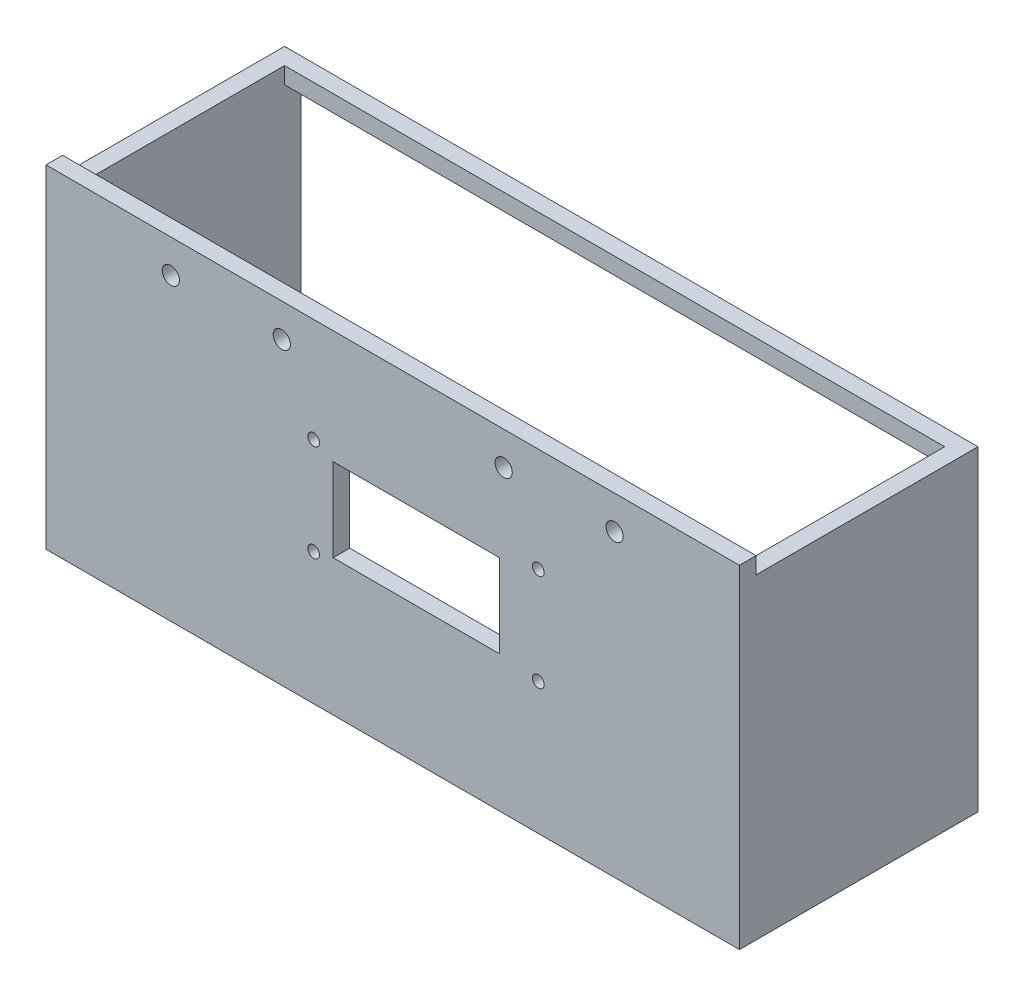
SolidWorks part; units mm, degrees
material "Thornel Mat VMA"
ref_plane "前视基准面" through (0, 0, 0) normal (0, 0, 1) x (1, 0, 0)
ref_plane "上视基准面" through (0, 0, 0) normal (0, 1, 0) x (1, 0, 0)
ref_plane "右视基准面" through (0, 0, 0) normal (1, 0, 0) x (0, 0, -1)
sketch "草图1" plane through (0, 0, 0) normal (0, 0, 1) x (1, 0, 0)
  line L1 (-62.5, 30) -> (62.5, 30)
  line L2 (-62.5, 30) -> (-62.5, -30)
  line L3 (-62.5, -30) -> (62.5, -30)
  line L4 (62.5, 30) -> (62.5, -30)
  line L5 (-62.5, 30) -> (62.5, -30) construction
  line L6 (-62.5, -30) -> (62.5, 30) construction
  line L7 (-14.25, 11.25) -> (26.25, 11.25) construction
  line L8 (-14.25, 11.25) -> (-14.25, -6.25) construction
  line L9 (-14.25, -6.25) -> (26.25, -6.25) construction
  line L10 (26.25, 11.25) -> (26.25, -6.25) construction
  line L11 (-10.75, 9.55) -> (19.25, 9.55)
  line L12 (-10.75, 9.55) -> (-10.75, -5.45)
  line L13 (-10.75, -5.45) -> (19.25, -5.45)
  line L14 (19.25, 9.55) -> (19.25, -5.45)
  line L15 (-10.75, 9.55) -> (19.25, -5.45) construction
  line L16 (-10.75, -5.45) -> (19.25, 9.55) construction
  circle A0 centre (-40, 24) radius 1.55
  circle A1 centre (-20, 24) radius 1.55
  circle A2 centre (20, 24) radius 1.55
  circle A3 centre (40, 24) radius 1.55
  circle A4 centre (-14.25, 11.25) radius 1.05
  circle A5 centre (-14.25, -6.25) radius 1.05
  circle A6 centre (26.25, 11.25) radius 1.05
  circle A7 centre (26.25, -6.25) radius 1.05
  point P0 (0, 0)
  point P22 (4.25, 2.05)
  dimension "D3" = 3.1
  dimension "D4" = 3.1
  dimension "D5" = 3.1
  dimension "D6" = 3.1
  dimension "D7" = 2.1
  dimension "D8" = 2.1
  dimension "D9" = 2.1
  dimension "D10" = 2.1
  dimension "D12" = 22.5
  dimension "D13" = 20
  dimension "D14" = 40
  dimension "D15" = 20
  dimension "D18" = 18.75
  dimension "D19" = 48.25
  dimension "D1" = 125
  dimension "D2" = 60
  dimension "D11" = 6
  dimension "D16" = 40.5
  dimension "D17" = 17.5
  dimension "D20" = 30
  dimension "D21" = 15
  dimension "D22" = 51.75
  dimension "D23" = 20.45
extrude "凸台-拉伸1" add sketch "草图1" along normal blind 3
ref_plane "基准面1" through (0, 0, 3) normal (0, 0, 1) x (1, 0, 0)
sketch "草图4" plane through (0, 0, 3) normal (0, 0, 1) x (1, 0, 0)
  line L1 (-62.5, -30) -> (-59.5, -30)
  line L2 (-62.5, -30) -> (-62.5, 27)
  line L3 (-62.5, 27) -> (-59.5, 27)
  line L4 (-59.5, -30) -> (-59.5, 27)
  line L6 (62.5, -30) -> (59.5, -30)
  line L7 (62.5, -30) -> (62.5, 27)
  line L8 (62.5, 27) -> (59.5, 27)
  line L9 (59.5, -30) -> (59.5, 27)
  point P12 (0, 0)
  point P13 (0, 0)
  point P14 (0, 0)
  dimension "D1" = 3
  dimension "D2" = 3
  dimension "D3" = 57
  dimension "D4" = 57
extrude "凸台-拉伸3" add sketch "草图4" against normal blind 43
ref_plane "基准面2" through (0, 30, 0) normal (0, 1, 0) x (1, 0, 0)
ref_plane "基准面3" through (0, 27, 0) normal (0, 1, 0) x (1, 0, 0)
sketch "草图6" plane through (0, 27, 0) normal (0, 1, 0) x (1, 0, 0)
  line L0 (62.5, 40) -> (62.5, 0) construction
  line L1 (-62.5, 40) -> (62.5, 40)
  line L2 (-62.5, 40) -> (-62.5, 37)
  line L3 (-62.5, 37) -> (62.5, 37)
  line L4 (62.5, 40) -> (62.5, 37)
  dimension "D1" = 3
extrude "凸台-拉伸5" add sketch "草图6" against normal blind 3
